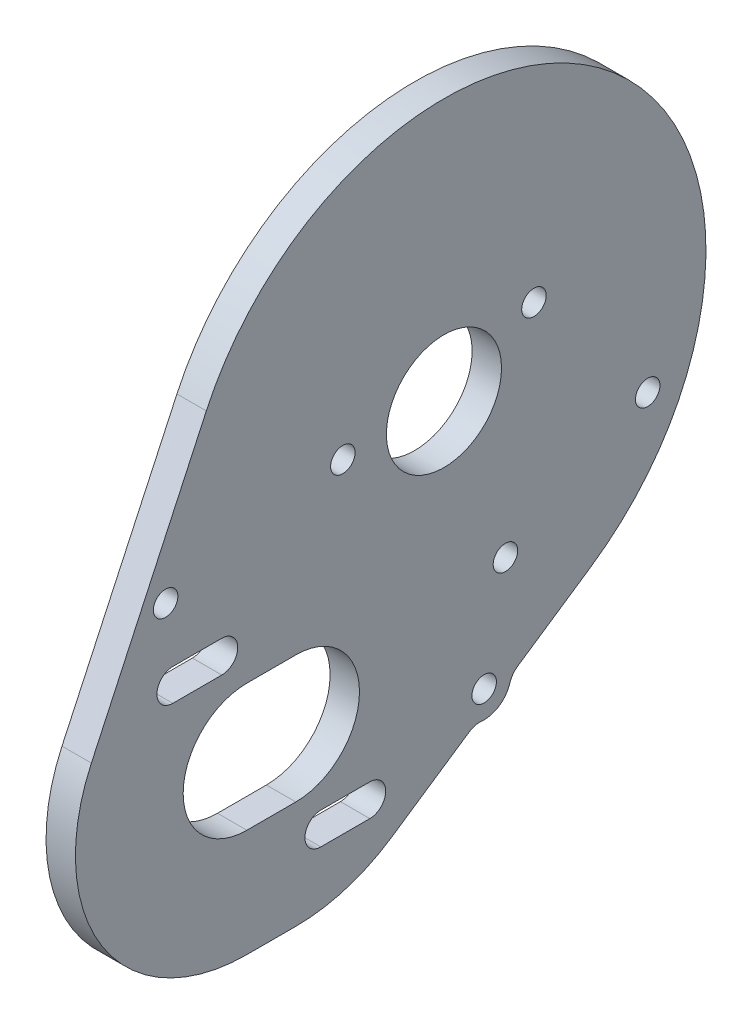
SolidWorks part; units mm, degrees
ref_plane "Front Plane" through (0, 0, 0) normal (0, 0, 1) x (1, 0, 0)
ref_plane "Top Plane" through (0, 0, 0) normal (0, 1, 0) x (1, 0, 0)
ref_plane "Right Plane" through (0, 0, 0) normal (1, 0, 0) x (0, 0, -1)
sketch "Sketch3" plane through (0, 0, 0) normal (1, 0, 0) x (0, 0, -1)
  line L0 (-20.125, -14.875) -> (-15.125, -14.875)
  line L1 (-15.125, -27.875) -> (-20.125, -27.875)
  line L2 (-26.625, -21.375) -> (-26.625, -12.1581) construction
  line L3 (-8.625, -21.375) -> (-8.625, -10.4698) construction
  line L4 (0, -5.875) -> (9.1895, -5.875) construction
  line L5 (-5.875, 0) -> (-5.875, 7.7787) construction
  line L6 (-24.2616, 11.2667) -> (-35.997, -14.0042)
  line L7 (-20.125, -38.875) -> (-15.125, -38.875)
  line L8 (14.9701, -22.1689) -> (7.5344, -27.19)
  line L9 (-37.625, -21.375) -> (-37.625, -11.278) construction
  line L10 (-22.6794, -9.625) -> (-27.6794, -9.625)
  line L11 (-27.6794, -12.875) -> (-22.6794, -12.875)
  line L12 (-7.5706, -29.875) -> (-12.5706, -29.875)
  line L13 (-12.5706, -33.125) -> (-7.5706, -33.125)
  line L14 (-12.5706, -31.5) -> (-27.6794, -11.25) construction
  line L15 (2.5524, -30.5542) -> (-5.3315, -35.878)
  circle A0 centre (0, 0) radius 5.875
  circle A1 centre (-20.125, -21.375) radius 6.5
  circle A2 centre (-15.125, -21.375) radius 6.5
  circle A3 centre (0, 0) radius 26.75
  arc A4 (-35.997, -14.0042) -> (-20.125, -38.875) centre (-20.125, -21.375) ccw
  arc A5 (-15.125, -38.875) -> (-5.3315, -35.878) centre (-15.125, -21.375) ccw
  circle A6 centre (-22.6794, -11.25) radius 1.625
  circle A7 centre (-27.6794, -11.25) radius 1.625
  circle A8 centre (-12.5706, -31.5) radius 1.625
  circle A9 centre (-7.5706, -31.5) radius 1.625
  circle A10 centre (-28.418, -3.6558) radius 1.25
  circle A11 centre (-10.3226, 0) radius 1.25
  circle A12 centre (9.1895, 4.1401) radius 1.25
  circle A13 centre (20.8005, -9.625) radius 1.25
  circle A14 centre (6.2776, -16.9583) radius 1.25
  circle A15 centre (4.1043, -27.4815) radius 1.25
  arc A16 (3.8538, -30.22) -> (6.7381, -28.2723) centre (4.1043, -27.4815) ccw
  arc A17 (2.5524, -30.5542) -> (3.8538, -30.22) centre (3.6716, -32.2117) cw
  arc A18 (6.7381, -28.2723) -> (7.5344, -27.19) centre (8.6536, -28.8475) cw
  point P62 (3.2378, -30.0914)
  dimension "D1" = 11.75
  dimension "D6" = 53.5
  dimension "D8" = 11
  dimension "D9" = 17.5
  dimension "D15" = 2.5
  dimension "D17" = 2.5
  dimension "D18" = 2.5
  dimension "D19" = 2.5
  dimension "D20" = 2.5
  dimension "D21" = 2.5
  dimension "D4" = 1.5
  dimension "D10" = 2
  dimension "D2" = 18
  dimension "D3" = 5
  dimension "D5" = 2.75
  dimension "D7" = 5
  dimension "D11" = 5
  dimension "D13" = 3.25
  dimension "D14" = 3.25
  dimension "D16" = 5
extrude "Boss-Extrude2" add sketch "Sketch3" along normal blind 3 separate body contours A15 A3 A2 A1 L11 A7 L10 L6 A4 L7 A5 L8 A10 A9 L13 A8 L12 | A15 A3 L10 A6 L11 A1 A2 A14 A13 A12 A11 A0
